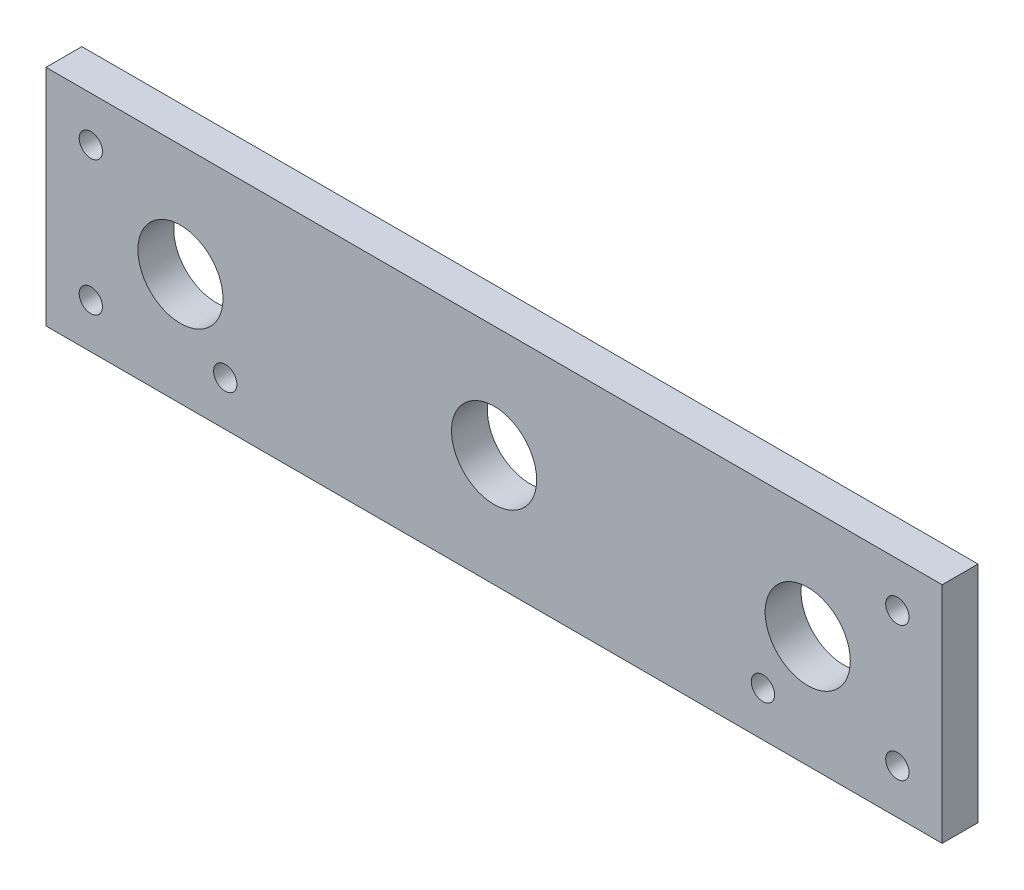
SolidWorks part; units mm, degrees
ref_plane "Ön Düzlem" through (0, 0, 0) normal (0, 0, 1) x (1, 0, 0)
ref_plane "Üst Düzlem" through (0, 0, 0) normal (0, 1, 0) x (1, 0, 0)
ref_plane "Sağ Düzlem" through (0, 0, 0) normal (1, 0, 0) x (0, 0, -1)
sketch "Çizim1" plane through (0, 0, 0) normal (0, 0, 1) x (1, 0, 0)
  line L0 (41.8502, -1.6887) -> (41.8502, -51.6887) construction
  line L1 (-58.1498, -1.6887) -> (141.8502, -1.6887)
  line L2 (-58.1498, -1.6887) -> (-58.1498, -51.6887)
  line L3 (-58.1498, -51.6887) -> (141.8502, -51.6887)
  line L4 (141.8502, -1.6887) -> (141.8502, -51.6887)
  circle A0 centre (-28.1498, -26.6887) radius 4
  circle A1 centre (-28.1498, -26.6887) radius 9.5
  circle A2 centre (111.8502, -26.6887) radius 4
  circle A3 centre (111.8502, -26.6887) radius 9.5
  circle A4 centre (-48.1498, -11.6887) radius 2.283
  circle A5 centre (-48.1498, -41.6887) radius 2.4763
  circle A6 centre (131.8502, -41.6887) radius 2.4763
  circle A7 centre (131.8502, -11.6887) radius 2.283
  dimension "D3" = 8
  dimension "D4" = 30
  dimension "D5" = 19
  dimension "D6" = 19
  dimension "D7" = 30
  dimension "D8" = 25
  dimension "D9" = 10
  dimension "D10" = 10
  dimension "D11" = 10
  dimension "D12" = 10
  dimension "D1" = 200
  dimension "D2" = 50
  dimension "25" = 25
extrude "Yükseklik-Ekstrüzyon1" add sketch "Çizim1" along normal blind 8 contours L1 L0 L3 L4 A7 A3 A6 | L0 L1 L2 L3 A5 A4 A1 | A4 | A5 | A7 | A6
hole_wizard "M5 Helisarmal için Zıvana matkabı1" positions "Çizim2" profile "Çizim3" hole size "M5x0.8" standard "ANSI Metric" end condition up to next
sketch "Çizim2" plane through (0, 0, 8) normal (0, 0, 1) x (1, 0, 0)
  point P0 (-48.1498, -11.6887)
  point P3 (-48.1498, -41.6887)
  point P6 (131.8502, -41.6887)
  point P9 (131.8502, -11.6887)
sketch "Çizim3" plane through (-48.1498, -11.6887, 8) normal (1, 0, 0) x (0, -1, 0)
  line L0 (0, 0) -> (0, 8)
  line L1 (0, 8) -> (2.6, 8)
  line L2 (2.6, 8) -> (2.6, 0)
  line L5 (2.6, 0) -> (0, 0)
  line L11 (0, -6.35) -> (0, 107.95) construction
  dimension "Thru Hole Dia." = 5.2
  dimension "Thru Hole Depth" = 8
sketch "Çizim5" plane through (0, 0, 8) normal (0, 0, 1) x (1, 0, 0)
  line L0 (-58.1498, -51.6887) -> (141.8502, -51.6887) construction
  line L1 (-58.1498, -1.6887) -> (-58.1498, -51.6887) construction
  line L2 (41.8502, -1.6887) -> (41.8502, -9.312) construction
  line L3 (-58.1498, -1.6887) -> (141.8502, -1.6887) construction
  circle A0 centre (-18.1498, -41.6887) radius 3.103
  circle A1 centre (101.8502, -41.6887) radius 3.103
  dimension "D1" = 10
  dimension "D2" = 40
hole_wizard "M5 Helisarmal için Zıvana matkabı2" positions "3B Çizim1" profile "Çizim6" hole size "M5x0.8" standard "ANSI Metric" end condition up to next
sketch3d "3B Çizim1"
  point P0 (-18.1498, -41.6887, 8)
  point P3 (101.8502, -41.6887, 8)
sketch "Çizim6" plane through (-18.1498, -41.6887, 8) normal (1, 0, 0) x (0, -1, 0)
  line L0 (0, 0) -> (0, 8)
  line L1 (0, 8) -> (2.6, 8)
  line L2 (2.6, 8) -> (2.6, 0)
  line L5 (2.6, 0) -> (0, 0)
  line L11 (0, -6.35) -> (0, 107.95) construction
  dimension "Thru Hole Dia." = 5.2
  dimension "Thru Hole Depth" = 8
sketch "Çizim7" plane through (0, 0, 8) normal (0, 0, 1) x (1, 0, 0)
  line L0 (41.8502, -1.6887) -> (41.8502, -51.6887)
  line L1 (-58.1498, -1.6887) -> (141.8502, -1.6887) construction
  line L2 (-58.1498, -51.6887) -> (141.8502, -51.6887) construction
  circle A0 centre (41.8502, -26.6887) radius 9.5
  dimension "D1" = 19
extrude "Kes-Ekstrüzyon1" cut sketch "Çizim7" against normal blind 10 contours L0 A0 | L0 A0
